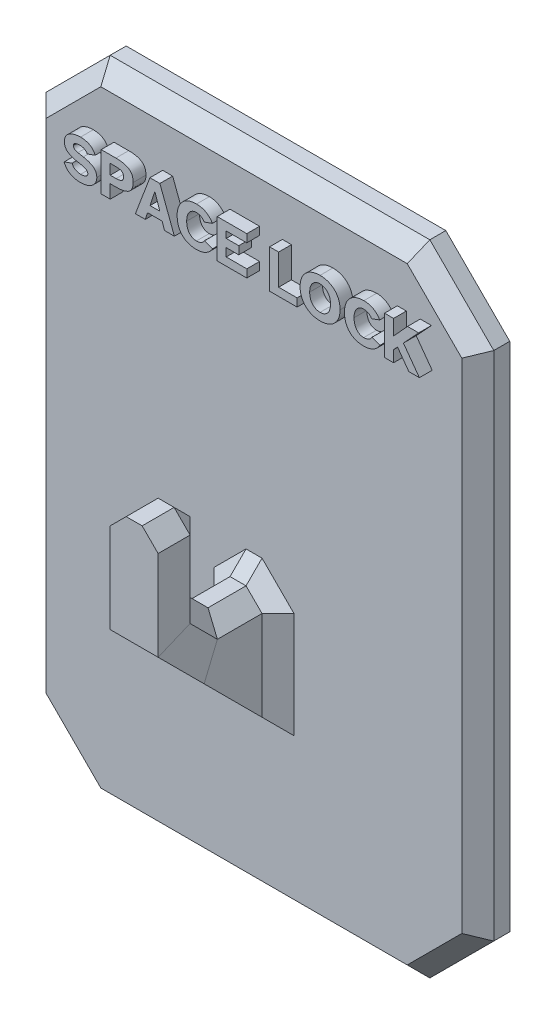
SolidWorks part; units mm, degrees
ref_plane "Front Plane" through (0, 0, 0) normal (0, 0, 1) x (1, 0, 0)
ref_plane "Top Plane" through (0, 0, 0) normal (0, 1, 0) x (1, 0, 0)
ref_plane "Right Plane" through (0, 0, 0) normal (1, 0, 0) x (0, 0, -1)
sketch "Sketch1" plane through (0, 0, 0) normal (0, 0, 1) x (1, 0, 0)
  line L1 (-35, -50) -> (35, -50)
  line L2 (-35, -50) -> (-35, 50)
  line L3 (-35, 50) -> (35, 50)
  line L4 (35, -50) -> (35, 50)
  line L5 (-35, -50) -> (35, 50) construction
  line L6 (-35, 50) -> (35, -50) construction
  point P0 (0, 0)
  dimension "D1" = 70
  dimension "D2" = 100
extrude "Boss-Extrude1" add sketch "Sketch1" along normal blind 5
sketch "Sketch2" plane through (0, 0, 5) normal (0, 0, 1) x (1, 0, 0)
  line L0 (-35, 0) -> (49965, 0) construction
  line L1 (-35, 50) -> (-35, -50) construction
  line L2 (35, -50) -> (35, 50) construction
  line L3 (0, -50) -> (0, 49950) construction
  line L8 (-35, -50) -> (35, -50) construction
  line L9 (35, 50) -> (-35, 50) construction
  line L11 (-3.75, -13.75) -> (3.75, -13.75)
  line L12 (-3.75, -13.75) -> (-3.75, -6.25)
  line L13 (-3.75, -6.25) -> (3.75, -6.25)
  line L14 (3.75, -13.75) -> (3.75, -6.25)
  line L15 (-3.75, -13.75) -> (3.75, -6.25) construction
  line L16 (-3.75, -6.25) -> (3.75, -13.75) construction
  point P4 (-35, 0)
  point P7 (35, 0)
  point P8 (0, -10)
  point P16 (0, -50)
  point P19 (0, 50)
  dimension "D1" = 7.5
  dimension "D2" = 10
sketch "Sketch3" plane through (0, 0, 0) normal (1, 0, 0) x (0, 0, -1)
  line L0 (-5, -10) -> (-15, -10)
  line L1 (-15, -10) -> (-20, -5)
  line L2 (-20, -5) -> (-20, 10)
  line L3 (-5, -200050) -> (-5, 249950) construction
  dimension "D1" = 15
  dimension "D2" = 45
  dimension "D3" = 5
  dimension "D4" = 15
sweep "Sweep1" add profiles "Sketch2" path "Sketch3"
sketch "Sketch4" plane through (0, 0, 5) normal (0, 0, 1) x (1, 0, 0)
  line L0 (-25, 50) -> (-35, 40)
  line L1 (35, 50) -> (-35, 50) construction
  line L2 (-35, 50) -> (-35, -50) construction
  line L3 (0, 0) -> (0, 50000) construction
  line L4 (0, 0) -> (-50000, 0) construction
  line L5 (-25, 50) -> (-35, 50)
  line L6 (-35, 50) -> (-35, 40)
  line L7 (25, 50) -> (35, 50)
  line L8 (25, 50) -> (35, 40)
  line L9 (35, 50) -> (35, 40)
  line L10 (25, -50) -> (35, -40)
  line L11 (35, -50) -> (35, -40)
  line L12 (25, -50) -> (35, -50)
  line L13 (-25, -50) -> (-35, -50)
  line L14 (-25, -50) -> (-35, -40)
  line L15 (-35, -50) -> (-35, -40)
  point P11 (0, 50)
  point P13 (-35, 0)
  dimension "D1" = 10
  dimension "D2" = 10
extrude "Cut-Extrude1" cut sketch "Sketch4" against normal through all both and the other way through all
sketch "Sketch6" plane through (-3.75, 0, 0) normal (-1, 0, 0) x (0, 0, 1)
  line L0 (16.5533, -13.75) -> (5, -25.3033)
  line L1 (5, 40) -> (5, -40) construction
  line L2 (16.5533, -13.75) -> (23.75, -6.5533) construction
  line L3 (5, -25.3033) -> (5, -13.75)
  line L4 (5, -13.75) -> (16.5533, -13.75)
extrude "Boss-Extrude2" add sketch "Sketch6" against normal up to surface (7.5 mm away) up to face at (3.75, -10, 10)
sketch "Sketch7" plane through (0, 0, 5) normal (0, 0, 1) x (1, 0, 0)
  line L0 (-35, 35) -> (35, 35) construction
  line L1 (-35, 40) -> (-35, -40) construction
  line L2 (35, -40) -> (35, 40) construction
  line L3 (25, 50) -> (-25, 50) construction
  text T0 "SPACE LOCK" font "Atkinson Hyperlegible" height 6
  dimension "D1" = 15
extrude "Boss-Extrude3" add sketch "Sketch7" along normal blind 2
chamfer "Chamfer1" distance 2.5 angle 45 20 edges at (3.75, 3.2767, 16.25) (3.75, -4.8483, 14.8483) (3.75, -6.25, 9.2233) (-3.75, 3.2767, 16.25) (-3.75, -4.8483, 14.8483) (-3.75, -6.25, 9.2233) (-3.75, -15.7767, 5) (0, -6.25, 5) (3.75, -15.7767, 5) (30, 45, 5) (0, 50, 5) (35, 0, 5) (30, -45, 5) (0, -50, 5) (-30, -45, 5) (-35, 0, 5) (-30, 45, 5) (0, 10, 16.25) (3.75, 10, 20) (-3.75, 10, 20)
